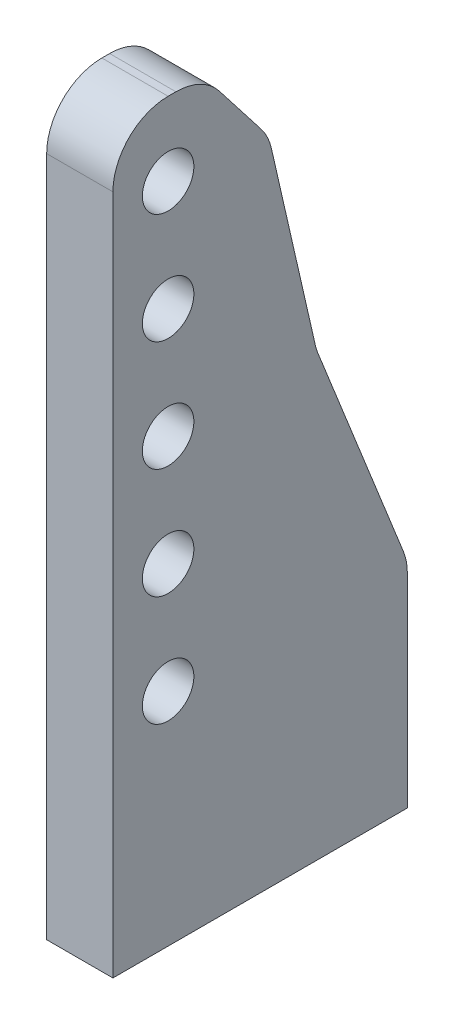
SolidWorks part; units mm, degrees
ref_plane "Front Plane" through (0, 0, 0) normal (0, 0, 1) x (1, 0, 0)
ref_plane "Top Plane" through (0, 0, 0) normal (0, 1, 0) x (1, 0, 0)
ref_plane "Right Plane" through (0, 0, 0) normal (1, 0, 0) x (0, 0, -1)
sketch "草圖1" plane through (0, 0, 0) normal (0, 1, 0) x (1, 0, 0)
  line L1 (0.9, -4) -> (-0.9, -4)
  line L2 (0.9, -4) -> (0.9, 4)
  line L3 (0.9, 4) -> (-0.9, 4)
  line L4 (-0.9, -4) -> (-0.9, 4)
  line L5 (0.9, -4) -> (-0.9, 4) construction
  line L6 (0.9, 4) -> (-0.9, -4) construction
  point P0 (0, 0)
  dimension "D1" = 1.8
  dimension "D2" = 8
extrude "填料-伸長1" add sketch "草圖1" along normal blind 20
sketch "草圖3" plane through (0.9, 0, 0) normal (1, 0, 0) x (0, 0, -1)
  line L0 (-4, 20) -> (-4, 0) construction
  line L1 (-4, 20) -> (4, 20) construction
  line L2 (-1.5543, 20) -> (0.2306, 17.7007)
  line L3 (0.2306, 17.7007) -> (1.5251, 12.0323)
  line L4 (1.5251, 12.0323) -> (4, 5.8224)
  line L5 (4, 20) -> (4, 0) construction
  line L6 (4, 5.8224) -> (4, 20)
  line L7 (4, 20) -> (-1.5543, 20)
  circle A0 centre (-2.5, 18) radius 0.7
  circle A1 centre (-2.5, 15) radius 0.7
  circle A2 centre (-2.5, 12) radius 0.7
  circle A3 centre (-2.5, 9) radius 0.7
  circle A4 centre (-2.5, 6) radius 0.7
  dimension "D3" = 1.4
  dimension "D1" = 1.5
  dimension "D2" = 2
  dimension "D4" = 5
extrude "除料-伸長1" cut sketch "草圖3" against normal blind 20
fillet "圓角1" radius 1.5 5 edges at (0, 5.8224, -4) (0, 12.0323, -1.5251) (0, 17.7007, -0.2306) (0, 20, 1.5543) (0, 20, 4)
